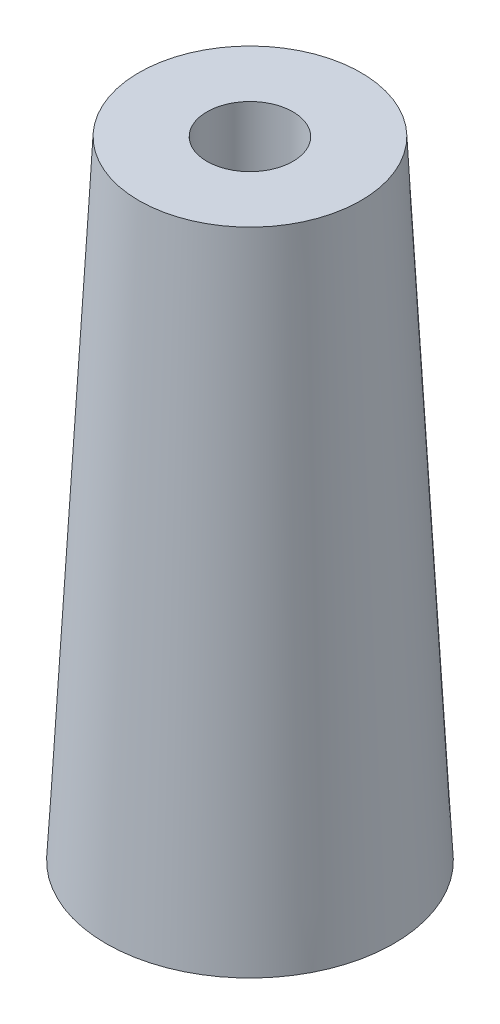
SolidWorks part; units mm, degrees
ref_plane "Front Plane" through (0, 0, 0) normal (0, 0, 1) x (1, 0, 0)
ref_plane "Top Plane" through (0, 0, 0) normal (0, 1, 0) x (1, 0, 0)
ref_plane "Right Plane" through (0, 0, 0) normal (1, 0, 0) x (0, 0, -1)
sketch "Sketch1" plane through (0, 0, 0) normal (0, 1, 0) x (1, 0, 0)
  circle A0 centre (0, 0) radius 6.35
  dimension "D1" = 12.7
extrude "Boss-Extrude1" add sketch "Sketch1" along normal blind 27.686 draft 3
hole_wizard "#10-24 Tapped Hole1" positions "Sketch2" profile "Sketch3" tap size "#10-24" standard "ANSI Inch"
sketch "Sketch2" plane through (0, 27.686, 0) normal (0, 1, 0) x (1, 0, 0)
  point P0 (0, 0)
sketch "Sketch3" plane through (0, 27.686, 0) normal (1, 0, 0) x (0, 0, 1)
  line L0 (0, 0) -> (0, 13.8408)
  line L1 (0, 13.8408) -> (1.8986, 12.7)
  line L2 (1.8986, 12.7) -> (1.8986, 0)
  line L5 (1.8986, 0) -> (0, 0)
  line L10 (0, 13.8408) -> (-1.8987, 12.7) construction
  line L11 (0, -6.35) -> (0, 107.95) construction
  dimension "Tap Drill Dia." = 3.7973
  dimension "Tap Drill Depth" = 12.7
  dimension "Drill Angle" = 118
